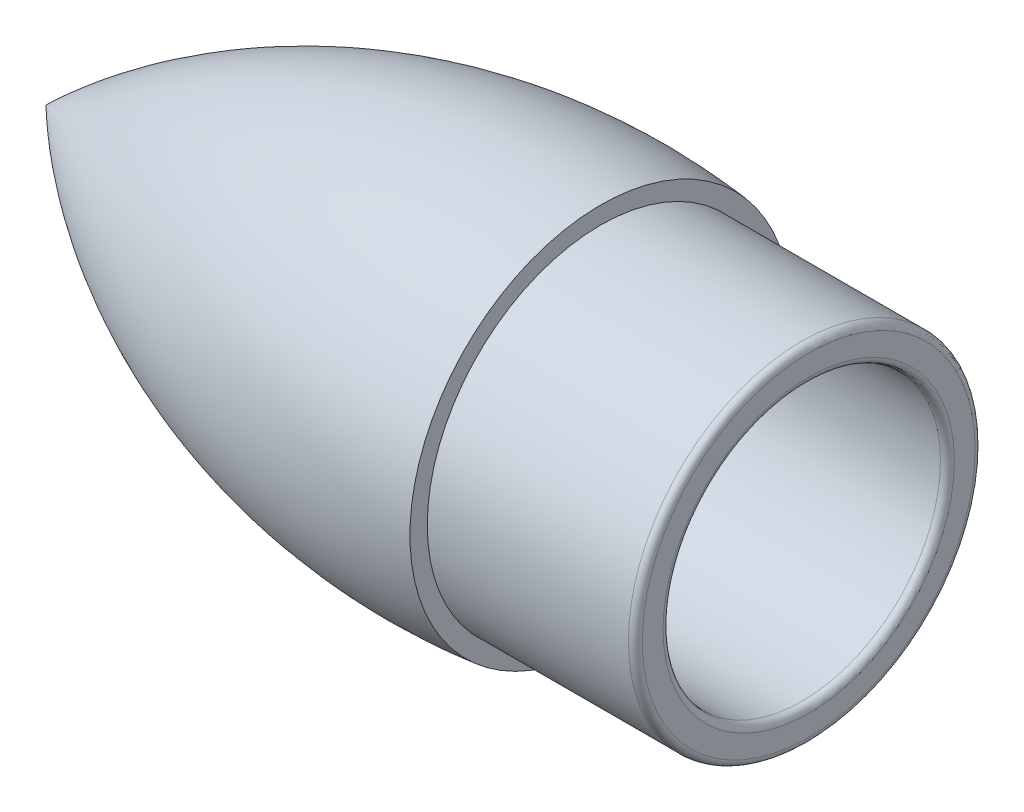
SolidWorks part; units mm, degrees
ref_plane "Front Plane" through (0, 0, 0) normal (0, 0, 1) x (1, 0, 0)
ref_plane "Top Plane" through (0, 0, 0) normal (0, 1, 0) x (1, 0, 0)
ref_plane "Right Plane" through (0, 0, 0) normal (1, 0, 0) x (0, 0, -1)
sketch "Sketch1" plane through (0, 0, 0) normal (0, 1, 0) x (1, 0, 0)
  line L0 (25, -25) -> (25, -27.5)
  line L1 (55, 27.5) -> (-55, 27.5)
  line L2 (55, 27.5) -> (55, -27.5)
  line L3 (55, -27.5) -> (-55, -27.5)
  line L4 (-55, 27.5) -> (-55, -27.5)
  line L5 (55, 27.5) -> (-55, -27.5) construction
  line L6 (55, -27.5) -> (-55, 27.5) construction
  line L7 (-55, -25) -> (55, -25)
  line L8 (-55, -25) -> (-55, 25)
  line L9 (-55, 25) -> (55, 25)
  line L10 (55, -25) -> (55, 25)
  line L11 (-55, -25) -> (55, 25) construction
  line L12 (-55, 25) -> (55, -25) construction
  line L13 (55, -25) -> (25, -25)
  line L14 (55, -25) -> (55, 25)
  line L15 (55, 25) -> (25, 25)
  line L16 (25, -25) -> (25, 25)
  line L17 (25, 25) -> (25, 27.5)
  line L18 (55, 0) -> (-55, 0)
  line L19 (-55, -27.5) -> (-75, -27.5)
  line L20 (-55, -27.5) -> (-55, 27.5)
  line L21 (-55, 27.5) -> (-75, 27.5)
  line L22 (-75, -27.5) -> (-75, 27.5)
  line L23 (-55, 0) -> (-50, 0)
  line L24 (-50, 0) -> (-40, 0)
  line L25 (25, -25) -> (20, -25)
  line L26 (25, -25) -> (25, -20)
  line L27 (25, -20) -> (20, -20)
  line L28 (20, -25) -> (20, -20)
  line L29 (25, -25) -> (55, -25)
  line L30 (25, -25) -> (25, -20)
  line L31 (25, -20) -> (55, -20)
  line L32 (55, -25) -> (55, -20)
  line L33 (25, -27.5) -> (20, -27.5)
  line L34 (25, -27.5) -> (25, -22.5)
  line L35 (25, -22.5) -> (20, -22.5)
  line L36 (20, -27.5) -> (20, -22.5)
  line L37 (-40, -27.5) -> (-40, 27.5)
  arc A0 (25, -27.5) -> (-75, 27.5) centre (14.321, 71.4927) cw
  arc A1 (25, -22.5) -> (-75, 27.5) centre (16.7216, 85.9432) cw
  point P0 (0, 0)
  point P6 (0, 0)
  point P17 (-55, 0)
  point P20 (-55, 0)
  point P35 (-40, 0)
  dimension "D1" = 55
  dimension "D2" = 110
  dimension "D3" = 50
  dimension "D4" = 30
  dimension "D5" = 20
  dimension "D6" = 5
  dimension "D7" = 5
  dimension "D8" = 5
  dimension "D9" = 5
  dimension "D10" = 10
revolve "Revolve3" add sketch "Sketch1" angle 360 about L18
fillet "Fillet1" radius 1 2 edges at (55, 0, -20) (55, 0, -25)
